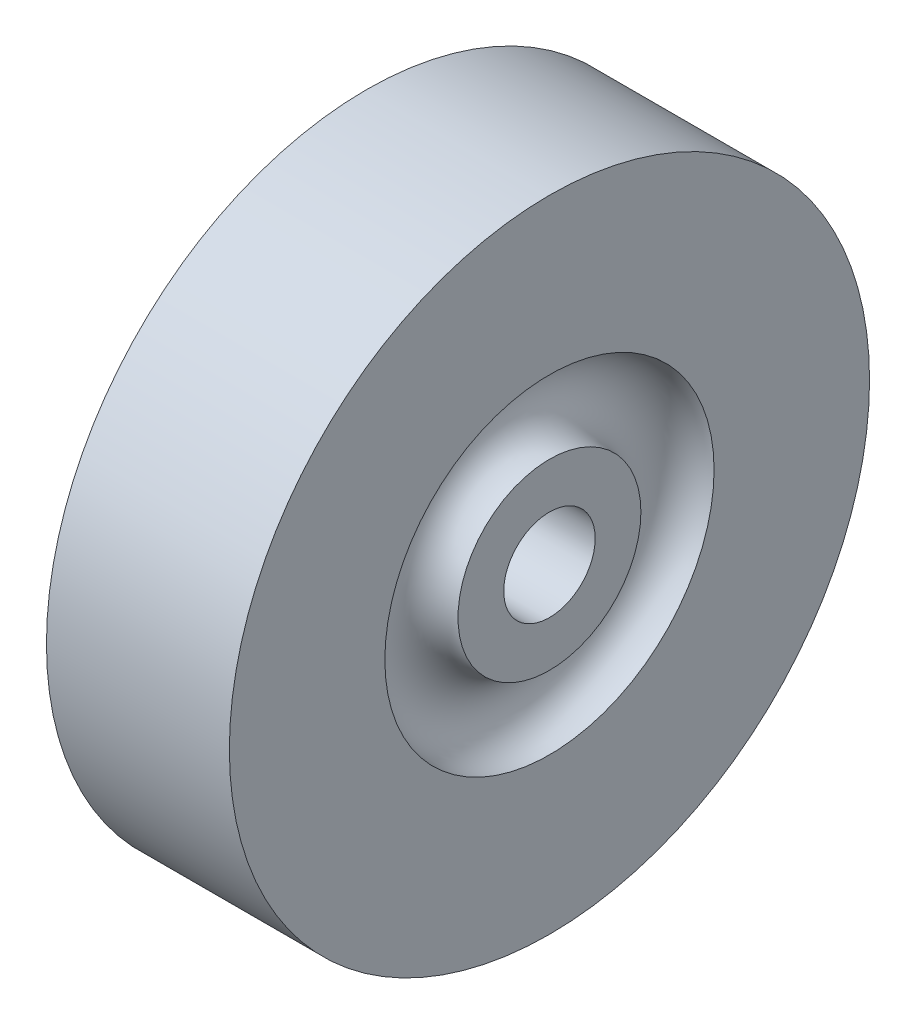
SolidWorks part; units mm, degrees
ref_plane "Front Plane" through (0, 0, 0) normal (0, 0, 1) x (1, 0, 0)
ref_plane "Top Plane" through (0, 0, 0) normal (0, 1, 0) x (1, 0, 0)
ref_plane "Right Plane" through (0, 0, 0) normal (1, 0, 0) x (0, 0, -1)
sketch "Sketch1" plane through (0, 0, 0) normal (0, 0, 1) x (1, 0, 0)
  line L0 (12.7, 0) -> (-12.7, 0) construction
  line L1 (12.7, 22.86) -> (12.7, 44.45)
  line L2 (12.7, 0) -> (12.7, 6.35) construction
  line L3 (12.7, 44.45) -> (-12.7, 44.45)
  line L4 (12.7, 6.35) -> (12.7, 12.7)
  line L5 (0, 44.45) -> (0, 0) construction
  line L6 (-12.7, 0) -> (-12.7, 6.35) construction
  line L7 (-12.7, 6.35) -> (-12.7, 12.7)
  line L8 (-12.7, 22.86) -> (-12.7, 44.45)
  line L9 (-12.7, 6.35) -> (12.7, 6.35)
  arc A0 (12.7, 12.7) -> (12.7, 22.86) centre (12.7, 17.78) cw
  arc A1 (-12.7, 12.7) -> (-12.7, 22.86) centre (-12.7, 17.78) ccw
  point P4 (0, 0)
  dimension "D3" = 5.08
  dimension "D1" = 12.7
  dimension "D2" = 6.35
  dimension "D4" = 6.35
  dimension "D5" = 44.45
revolve "Revolve1" add sketch "Sketch1" angle 360 about L0
